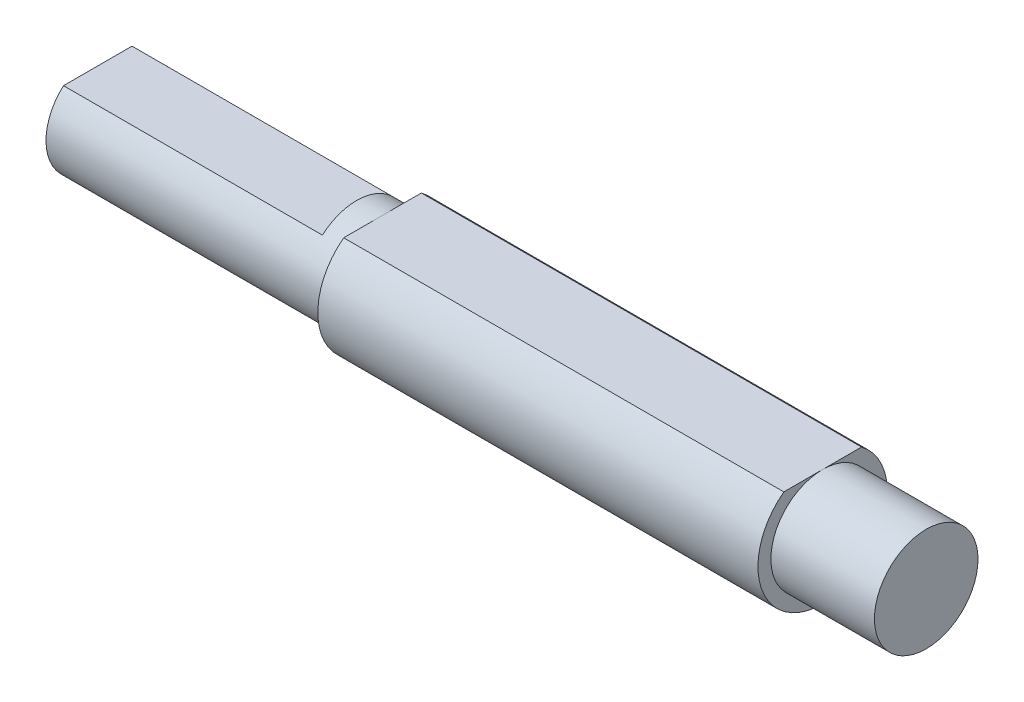
SolidWorks part; units mm, degrees
ref_plane "Piano frontale" through (0, 0, 0) normal (0, 0, 1) x (1, 0, 0)
ref_plane "Piano superiore" through (0, 0, 0) normal (0, 1, 0) x (1, 0, 0)
ref_plane "Piano destro" through (0, 0, 0) normal (1, 0, 0) x (0, 0, -1)
sketch "Sketch1" plane through (0, 0, 0) normal (0, 1, 0) x (1, 0, 0)
  circle A1 centre (0, 0) radius 2
extrude "Boss-Extrude1" add sketch "Sketch1" along normal blind 4
sketch "Sketch2" plane through (0, 4, 0) normal (0, 1, 0) x (1, 0, 0)
  circle A0 centre (0, 0) radius 2.5
extrude "Boss-Extrude2" add sketch "Sketch2" along normal blind 17
sketch "Sketch3" plane through (0, 21, 0) normal (0, 1, 0) x (1, 0, 0)
  line L2 (1.5, 2) -> (-1.5, 2)
  arc A0 (1.5, 2) -> (-1.5, 2) centre (0, 0) ccw
extrude "Cut-Extrude1" cut sketch "Sketch3" against normal blind 17
sketch "Sketch4" plane through (0, 21, 0) normal (0, 1, 0) x (1, 0, 0)
  circle A0 centre (0, 0) radius 2
extrude "Boss-Extrude3" add sketch "Sketch4" along normal blind 11
move or copy body "Body-Move/Copy3" bodies to move or copy 104 copy no rotation origin (0, 15.5, 0) rotation axis (0, 0, 1) rotation angle 90
move or copy body "Body-Move/Copy5" bodies to move or copy 107 copy no rotation origin (0, 15.5, 0.25) rotation axis (1, 0, 0) rotation angle 90
sketch "Sketch5" plane through (-16.5, 0, 0) normal (-1, 0, 0) x (0, 0, 1)
  line L2 (-1.0729, 17.25) -> (1.5729, 17.25)
  circle A0 centre (0.25, 15.75) radius 2 construction
  arc A1 (1.5729, 17.25) -> (-1.0729, 17.25) centre (0.25, 15.75) ccw
extrude "Cut-Extrude2" cut sketch "Sketch5" against normal blind 10
